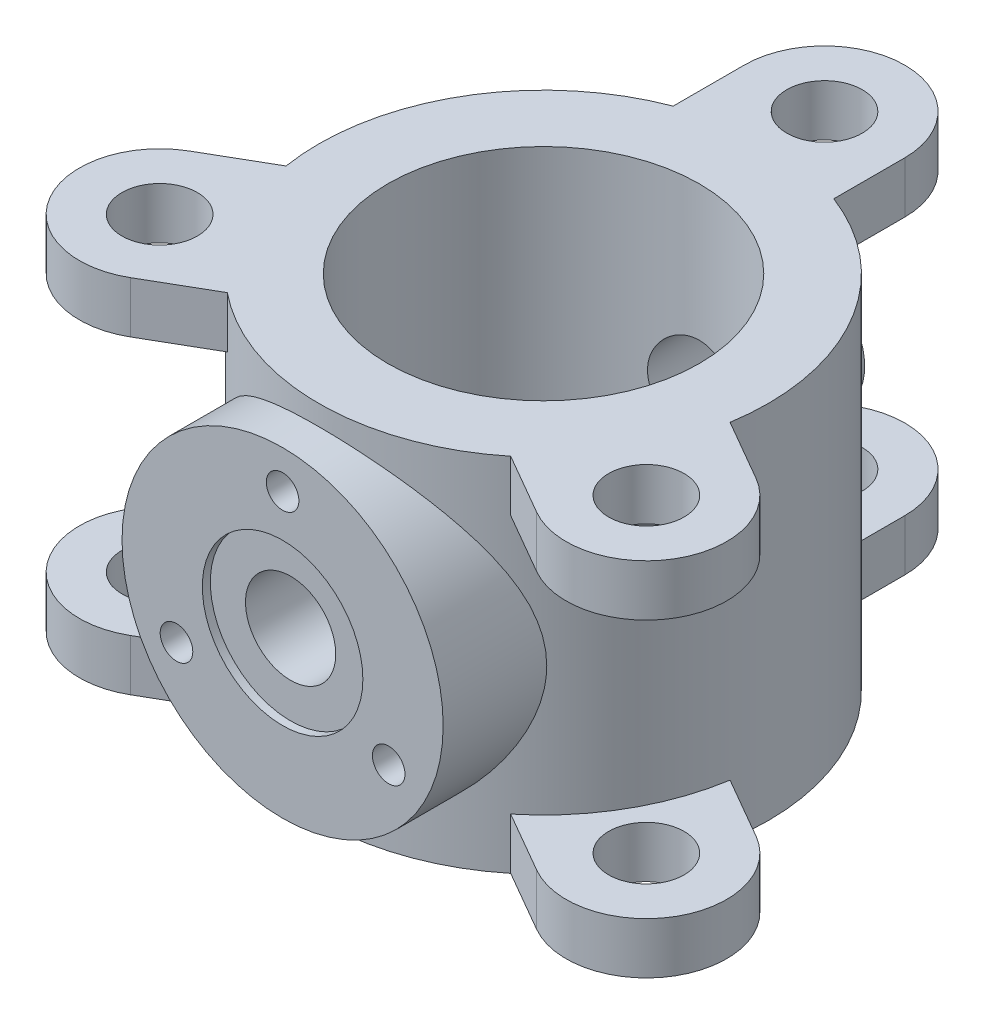
SolidWorks part; units mm, degrees
ref_plane "Front Plane" through (0, 0, 0) normal (0, 0, 1) x (1, 0, 0)
ref_plane "Top Plane" through (0, 0, 0) normal (0, 1, 0) x (1, 0, 0)
ref_plane "Right Plane" through (0, 0, 0) normal (1, 0, 0) x (0, 0, -1)
sketch "Sketch1" plane through (0, 0, 0) normal (0, 1, 0) x (1, 0, 0)
  circle A0 centre (0, 0) radius 140
  circle A1 centre (0, 0) radius 97
  dimension "D1" = 280
  dimension "D2" = 194
extrude "Boss-Extrude1" add sketch "Sketch1" along normal mid plane 225
ref_plane "Plane1" through (0, 0, 162.5) normal (0, 0, 1) x (1, 0, 0)
sketch "Sketch2" plane through (0, 0, 162.5) normal (0, 0, 1) x (1, 0, 0)
  circle A0 centre (0, 0) radius 100
  dimension "D1" = 200
extrude "Boss-Extrude2" add sketch "Sketch2" against normal up to next
ref_plane "Plane2" through (0, 0, -162.5) normal (0, 0, 1) x (1, 0, 0)
sketch "Sketch3" plane through (0, 0, -162.5) normal (0, 0, 1) x (1, 0, 0)
  circle A0 centre (0, 0) radius 37.5
  dimension "D1" = 75
extrude "Boss-Extrude3" add sketch "Sketch3" along normal up to next
hole_wizard "Hole1" positions "Sketch4" profile "Sketch5" legacy
sketch "Sketch4" plane through (0, 0, 162.5) normal (0, 0, 1) x (1, 0, 0)
  point P0 (0, 76.3)
  dimension "D1" = 76.3
sketch "Sketch5" plane through (0, 76.3, 162.5) normal (1, 0, 0) x (0, -1, 0)
  line L0 (0, 0) -> (0, 30)
  line L1 (0, 30) -> (10.15, 30)
  line L2 (10.15, 30) -> (10.15, 0)
  line L3 (10.15, 0) -> (0, 0)
  line L4 (0, 110) -> (0, -10) construction
  dimension "Diameter" = 20.3
  dimension "Depth" = 30
pattern_circular "CirPattern1" count 3 over 360 about axis through (0, 0, 0) along (0, 0, 1) of "Hole1"
hole_wizard "Hole2" positions "Sketch6" profile "Sketch7" legacy
sketch "Sketch6" plane through (0, 0, 162.5) normal (0, 0, 1) x (1, 0, 0)
  point P0 (0, 0)
sketch "Sketch7" plane through (0, 0, 162.5) normal (1, 0, 0) x (0, -1, 0)
  line L0 (0, 0) -> (0, 310)
  line L1 (0, 310) -> (28.1, 310)
  line L2 (28.1, 310) -> (28.1, 5)
  line L3 (28.1, 5) -> (50, 5)
  line L4 (50, 5) -> (50, 0)
  line L5 (50, 0) -> (0, 0)
  line L6 (0, 110) -> (0, -10) construction
  dimension "Diameter" = 56.2
  dimension "Depth" = 310
  dimension "C-Bore Diameter" = 100
  dimension "C-Bore Depth" = 5
sketch "Sketch8" plane through (0, 112.5, 0) normal (0, 1, 0) x (1, 0, 0)
  line L0 (-50, 175) -> (-50, 130.767)
  line L2 (50, 130.767) -> (50, 175)
  arc A0 (50, 175) -> (-50, 175) centre (0, 175) ccw
  circle A1 centre (0, 0) radius 140 construction
  arc A2 (50, 130.767) -> (-50, 130.767) centre (0, 0) ccw
  dimension "D2" = 100
  dimension "D1" = 175
extrude "Boss-Extrude4" add sketch "Sketch8" against normal blind 32
pattern_circular "CirPattern2" count 3 over 360 about axis through (0, 0, 0) along (0, 1, 0) of "Boss-Extrude4"
hole_wizard "Hole3" positions "Sketch9" profile "Sketch10" legacy
sketch "Sketch9" plane through (0, 112.5, 0) normal (0, 1, 0) x (1, 0, 0)
  point P0 (0, 175)
  point P4 (-151.5544, -87.5)
  point P7 (151.5544, -87.5)
sketch "Sketch10" plane through (0, 112.5, -175) normal (1, 0, 0) x (0, 0, 1)
  line L0 (0, 0) -> (0, 32)
  line L1 (0, 32) -> (23.5, 32)
  line L2 (23.5, 32) -> (23.5, 0)
  line L3 (23.5, 0) -> (0, 0)
  line L4 (0, 110) -> (0, -10) construction
  dimension "Diameter" = 47
  dimension "Depth" = 32
mirror "Mirror1" about plane through (0, 0, 0) normal (0, 1, 0) of "CirPattern2", "Hole3", "Boss-Extrude4"
